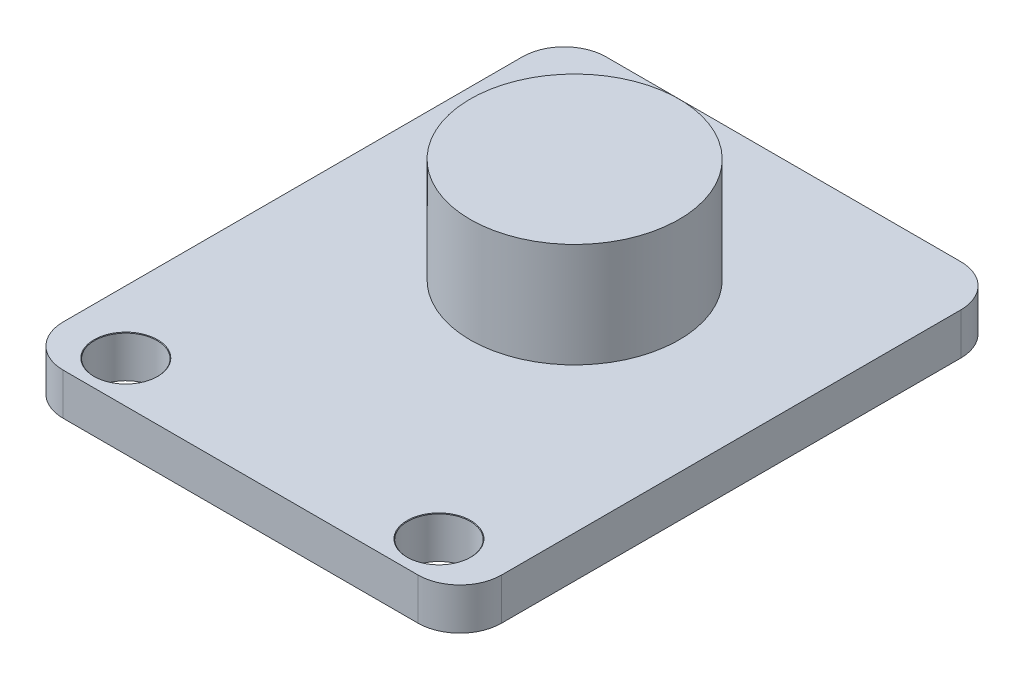
SolidWorks part; units mm, degrees
ref_plane "Front Plane" through (0, 0, 0) normal (0, 0, 1) x (1, 0, 0)
ref_plane "Top Plane" through (0, 0, 0) normal (0, 1, 0) x (1, 0, 0)
ref_plane "Right Plane" through (0, 0, 0) normal (1, 0, 0) x (0, 0, -1)
sketch "Sketch1" plane through (0, 0, 0) normal (0, 1, 0) x (1, 0, 0)
  line L1 (-10.5, 13) -> (10.5, 13)
  line L2 (-10.5, 13) -> (-10.5, -13)
  line L3 (-10.5, -13) -> (10.5, -13)
  line L4 (10.5, 13) -> (10.5, -13)
  line L5 (-10.5, 13) -> (10.5, -13) construction
  line L6 (-10.5, -13) -> (10.5, 13) construction
  point P0 (0, 0)
  dimension "D1" = 21
  dimension "D2" = 26
extrude "Boss-Extrude1" add sketch "Sketch1" along normal blind 2
fillet "Fillet1" radius 2 4 edges at (-10.5, 1, -13) (10.5, 1, -13) (-10.5, 1, 13) (10.5, 1, 13)
sketch "Sketch2" plane through (0, 2, 0) normal (0, 1, 0) x (1, 0, 0)
  line L0 (0, 3) -> (0, 0) construction
  circle A0 centre (0, 3) radius 5
  dimension "D2" = 10
  dimension "D1" = 3
extrude "Boss-Extrude2" add sketch "Sketch2" along normal blind 5
hole_wizard "Ø3.0 (3) Diameter Hole1" positions "Sketch3" profile "Sketch4" hole size "Ø3.0" standard "ISO" end condition through all
sketch "Sketch3" plane through (0, 2, 0) normal (0, 1, 0) x (1, 0, 0)
  line L0 (0, 0) -> (0, -11) construction
  line L2 (-7.5, -11) -> (7.5, -11) construction
  line L4 (10.5, -11) -> (7.5, -11) construction
  point P0 (-7.5, -11)
  point P2 (7.5, -11)
  dimension "D1" = 15
sketch "Sketch4" plane through (-7.5, 2, 11) normal (1, 0, 0) x (0, 0, 1)
  line L0 (0, 0) -> (0, 2)
  line L1 (0, 2) -> (1.5, 2)
  line L2 (1.5, 2) -> (1.5, 0.025)
  line L3 (1.5, 0.025) -> (1.525, 0)
  line L5 (1.525, 0) -> (0, 0)
  line L6 (-1.5, 0.025) -> (-1.525, 0) construction
  line L11 (0, -6.35) -> (0, 107.95) construction
  dimension "Thru Hole Dia." = 3
  dimension "Thru Hole Depth" = 2
  dimension "Near C'Sink Dia." = 3.05
  dimension "Near C'Sink Angle" = 90
